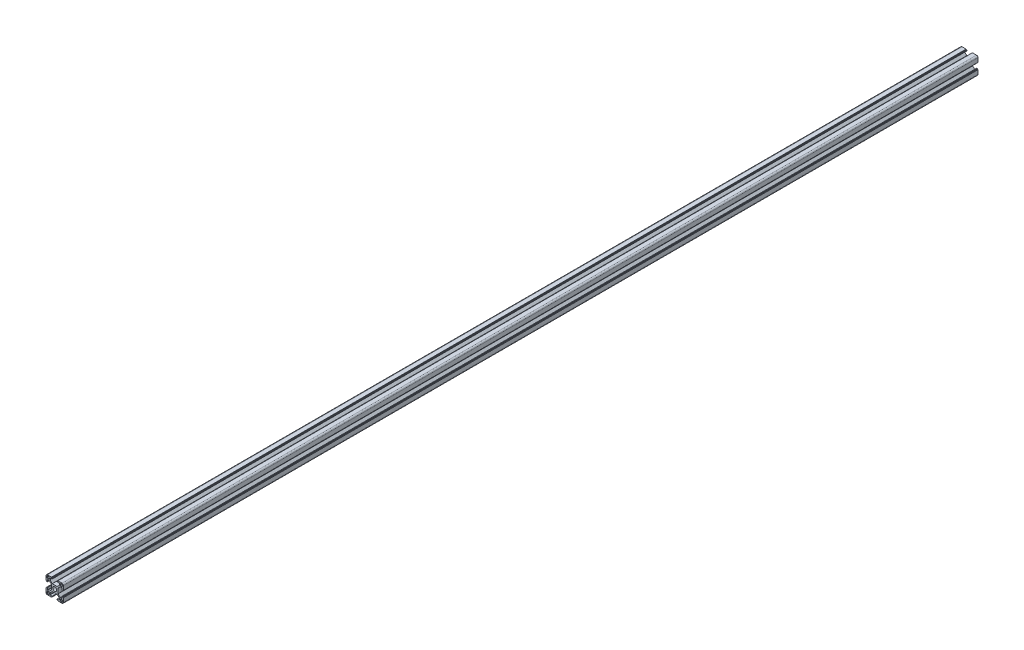
SolidWorks part; units mm, degrees
ref_plane "Front Plane" through (0, 0, 0) normal (0, 0, 1) x (1, 0, 0)
ref_plane "Top Plane" through (0, 0, 0) normal (0, 1, 0) x (1, 0, 0)
ref_plane "Right Plane" through (0, 0, 0) normal (1, 0, 0) x (0, 0, -1)
sketch "Model" plane through (0, 0, 0) normal (0, 0, 1) x (1, 0, 0)
  line L0 (21.5, 27) -> (25, 27)
  line L1 (27, 25) -> (27, 21.5)
  line L2 (25, 19.5) -> (21.5, 19.5)
  line L3 (19.5, 21.5) -> (19.5, 25)
  line L4 (21.5, -27) -> (25, -27)
  line L5 (27, -25) -> (27, -21.5)
  line L6 (25, -19.5) -> (21.5, -19.5)
  line L7 (19.5, -21.5) -> (19.5, -25)
  line L8 (0, 11.6) -> (-8.2402, 11.6)
  line L9 (-8.6645, 11.7757) -> (-16.3243, 19.4355)
  line L10 (-16.5, 19.8598) -> (-16.5, 25)
  line L11 (-15.9, 25.6) -> (-8.8, 25.6)
  line L12 (-8.2, 26.2) -> (-8.2, 27.4)
  line L13 (-8.8, 28) -> (-9.8, 28)
  line L14 (-10.4, 28.6) -> (-10.4, 29.4)
  line L15 (-11, 30) -> (-25, 30)
  line L16 (-30, 25) -> (-30, 11)
  line L17 (-29.4, 10.4) -> (-28.6, 10.4)
  line L18 (-28, 9.8) -> (-28, 8.8)
  line L19 (-27.4, 8.2) -> (-26.2, 8.2)
  line L20 (-25.6, 8.8) -> (-25.6, 15.9)
  line L21 (-25, 16.5) -> (-19.8598, 16.5)
  line L22 (-19.4355, 16.3243) -> (-11.7757, 8.6645)
  line L23 (-11.6, 8.2402) -> (-11.6, 0)
  line L24 (-11.6, 0) -> (-11.6, -8.2402)
  line L25 (-11.7757, -8.6645) -> (-19.4355, -16.3243)
  line L26 (-19.8598, -16.5) -> (-25, -16.5)
  line L27 (-25.6, -15.9) -> (-25.6, -8.8)
  line L28 (-26.2, -8.2) -> (-27.4, -8.2)
  line L29 (-28, -8.8) -> (-28, -9.8)
  line L30 (-28.6, -10.4) -> (-29.4, -10.4)
  line L31 (-30, -11) -> (-30, -25)
  line L32 (-25, -30) -> (-11, -30)
  line L33 (-10.4, -29.4) -> (-10.4, -28.6)
  line L34 (-9.8, -28) -> (-8.8, -28)
  line L35 (-8.2, -27.4) -> (-8.2, -26.2)
  line L36 (-8.8, -25.6) -> (-15.9, -25.6)
  line L37 (-16.5, -25) -> (-16.5, -19.8598)
  line L38 (-16.3243, -19.4355) -> (-8.6645, -11.7757)
  line L39 (-8.2402, -11.6) -> (0, -11.6)
  line L40 (0, -11.6) -> (8.2402, -11.6)
  line L41 (8.6645, -11.7757) -> (16.3243, -19.4355)
  line L42 (16.5, -19.8598) -> (16.5, -25)
  line L43 (15.9, -25.6) -> (8.8, -25.6)
  line L44 (8.2, -26.2) -> (8.2, -27.4)
  line L45 (8.8, -28) -> (9.8, -28)
  line L46 (10.4, -28.6) -> (10.4, -29.4)
  line L47 (11, -30) -> (25, -30)
  line L48 (30, -25) -> (30, -11)
  line L49 (29.4, -10.4) -> (28.6, -10.4)
  line L50 (28, -9.8) -> (28, -8.8)
  line L51 (27.4, -8.2) -> (26.2, -8.2)
  line L52 (25.6, -8.8) -> (25.6, -15.9)
  line L53 (25, -16.5) -> (19.8598, -16.5)
  line L54 (19.4355, -16.3243) -> (11.7757, -8.6645)
  line L55 (11.6, -8.2402) -> (11.6, 0)
  line L56 (11.6, 0) -> (11.6, 8.2402)
  line L57 (11.7757, 8.6645) -> (19.6113, 16.5)
  line L58 (19.6113, 16.5) -> (25, 16.5)
  line L59 (25.6, 15.9) -> (25.6, 8.8)
  line L60 (26.2, 8.2) -> (27.4, 8.2)
  line L61 (28, 8.8) -> (28, 9.8)
  line L62 (28.6, 10.4) -> (29.4, 10.4)
  line L63 (30, 11) -> (30, 25)
  line L64 (25, 30) -> (11, 30)
  line L65 (10.4, 29.4) -> (10.4, 28.6)
  line L66 (9.8, 28) -> (8.8, 28)
  line L67 (8.2, 27.4) -> (8.2, 26.2)
  line L68 (8.8, 25.6) -> (15.9, 25.6)
  line L69 (16.5, 25) -> (16.5, 19.8598)
  line L70 (16.3243, 19.4355) -> (8.6645, 11.7757)
  line L71 (8.2402, 11.6) -> (0, 11.6)
  line L72 (-21.5, -27) -> (-25, -27)
  line L73 (-27, -25) -> (-27, -21.5)
  line L74 (-25, -19.5) -> (-21.5, -19.5)
  line L75 (-19.5, -21.5) -> (-19.5, -25)
  line L76 (-21.5, 27) -> (-25, 27)
  line L77 (-27, 25) -> (-27, 21.5)
  line L78 (-25, 19.5) -> (-21.5, 19.5)
  line L79 (-19.5, 21.5) -> (-19.5, 25)
  circle A0 centre (0, 0) radius 6.8
  arc A1 (21.5, 27) -> (19.5, 25) centre (21.5, 25) ccw
  arc A2 (27, 25) -> (25, 27) centre (25, 25) ccw
  arc A3 (25, 19.5) -> (27, 21.5) centre (25, 21.5) ccw
  arc A4 (19.5, 21.5) -> (21.5, 19.5) centre (21.5, 21.5) ccw
  arc A5 (19.5, -25) -> (21.5, -27) centre (21.5, -25) ccw
  arc A6 (25, -27) -> (27, -25) centre (25, -25) ccw
  arc A7 (27, -21.5) -> (25, -19.5) centre (25, -21.5) ccw
  arc A8 (21.5, -19.5) -> (19.5, -21.5) centre (21.5, -21.5) ccw
  arc A9 (-8.6645, 11.7757) -> (-8.2402, 11.6) centre (-8.2402, 12.2) ccw
  arc A10 (-16.5, 19.8598) -> (-16.3243, 19.4355) centre (-15.9, 19.8598) ccw
  arc A11 (-15.9, 25.6) -> (-16.5, 25) centre (-15.9, 25) ccw
  arc A12 (-8.8, 25.6) -> (-8.2, 26.2) centre (-8.8, 26.2) ccw
  arc A13 (-8.2, 27.4) -> (-8.8, 28) centre (-8.8, 27.4) ccw
  arc A14 (-10.4, 28.6) -> (-9.8, 28) centre (-9.8, 28.6) ccw
  arc A15 (-10.4, 29.4) -> (-11, 30) centre (-11, 29.4) ccw
  arc A16 (-25, 30) -> (-30, 25) centre (-25, 25) ccw
  arc A17 (-30, 11) -> (-29.4, 10.4) centre (-29.4, 11) ccw
  arc A18 (-28, 9.8) -> (-28.6, 10.4) centre (-28.6, 9.8) ccw
  arc A19 (-28, 8.8) -> (-27.4, 8.2) centre (-27.4, 8.8) ccw
  arc A20 (-26.2, 8.2) -> (-25.6, 8.8) centre (-26.2, 8.8) ccw
  arc A21 (-25, 16.5) -> (-25.6, 15.9) centre (-25, 15.9) ccw
  arc A22 (-19.4355, 16.3243) -> (-19.8598, 16.5) centre (-19.8598, 15.9) ccw
  arc A23 (-11.6, 8.2402) -> (-11.7757, 8.6645) centre (-12.2, 8.2402) ccw
  arc A24 (-11.7757, -8.6645) -> (-11.6, -8.2402) centre (-12.2, -8.2402) ccw
  arc A25 (-19.8598, -16.5) -> (-19.4355, -16.3243) centre (-19.8598, -15.9) ccw
  arc A26 (-25.6, -15.9) -> (-25, -16.5) centre (-25, -15.9) ccw
  arc A27 (-25.6, -8.8) -> (-26.2, -8.2) centre (-26.2, -8.8) ccw
  arc A28 (-27.4, -8.2) -> (-28, -8.8) centre (-27.4, -8.8) ccw
  arc A29 (-28.6, -10.4) -> (-28, -9.8) centre (-28.6, -9.8) ccw
  arc A30 (-29.4, -10.4) -> (-30, -11) centre (-29.4, -11) ccw
  arc A31 (-30, -25) -> (-25, -30) centre (-25, -25) ccw
  arc A32 (-11, -30) -> (-10.4, -29.4) centre (-11, -29.4) ccw
  arc A33 (-9.8, -28) -> (-10.4, -28.6) centre (-9.8, -28.6) ccw
  arc A34 (-8.8, -28) -> (-8.2, -27.4) centre (-8.8, -27.4) ccw
  arc A35 (-8.2, -26.2) -> (-8.8, -25.6) centre (-8.8, -26.2) ccw
  arc A36 (-16.5, -25) -> (-15.9, -25.6) centre (-15.9, -25) ccw
  arc A37 (-16.3243, -19.4355) -> (-16.5, -19.8598) centre (-15.9, -19.8598) ccw
  arc A38 (-8.2402, -11.6) -> (-8.6645, -11.7757) centre (-8.2402, -12.2) ccw
  arc A39 (8.6645, -11.7757) -> (8.2402, -11.6) centre (8.2402, -12.2) ccw
  arc A40 (16.5, -19.8598) -> (16.3243, -19.4355) centre (15.9, -19.8598) ccw
  arc A41 (15.9, -25.6) -> (16.5, -25) centre (15.9, -25) ccw
  arc A42 (8.8, -25.6) -> (8.2, -26.2) centre (8.8, -26.2) ccw
  arc A43 (8.2, -27.4) -> (8.8, -28) centre (8.8, -27.4) ccw
  arc A44 (10.4, -28.6) -> (9.8, -28) centre (9.8, -28.6) ccw
  arc A45 (10.4, -29.4) -> (11, -30) centre (11, -29.4) ccw
  arc A46 (25, -30) -> (30, -25) centre (25, -25) ccw
  arc A47 (30, -11) -> (29.4, -10.4) centre (29.4, -11) ccw
  arc A48 (28, -9.8) -> (28.6, -10.4) centre (28.6, -9.8) ccw
  arc A49 (28, -8.8) -> (27.4, -8.2) centre (27.4, -8.8) ccw
  arc A50 (26.2, -8.2) -> (25.6, -8.8) centre (26.2, -8.8) ccw
  arc A51 (25, -16.5) -> (25.6, -15.9) centre (25, -15.9) ccw
  arc A52 (19.4355, -16.3243) -> (19.8598, -16.5) centre (19.8598, -15.9) ccw
  arc A53 (11.6, -8.2402) -> (11.7757, -8.6645) centre (12.2, -8.2402) ccw
  arc A54 (11.7757, 8.6645) -> (11.6, 8.2402) centre (12.2, 8.2402) ccw
  arc A55 (25.6, 15.9) -> (25, 16.5) centre (25, 15.9) ccw
  arc A56 (25.6, 8.8) -> (26.2, 8.2) centre (26.2, 8.8) ccw
  arc A57 (27.4, 8.2) -> (28, 8.8) centre (27.4, 8.8) ccw
  arc A58 (28.6, 10.4) -> (28, 9.8) centre (28.6, 9.8) ccw
  arc A59 (29.4, 10.4) -> (30, 11) centre (29.4, 11) ccw
  arc A60 (30, 25) -> (25, 30) centre (25, 25) ccw
  arc A61 (11, 30) -> (10.4, 29.4) centre (11, 29.4) ccw
  arc A62 (9.8, 28) -> (10.4, 28.6) centre (9.8, 28.6) ccw
  arc A63 (8.8, 28) -> (8.2, 27.4) centre (8.8, 27.4) ccw
  arc A64 (8.2, 26.2) -> (8.8, 25.6) centre (8.8, 26.2) ccw
  arc A65 (16.5, 25) -> (15.9, 25.6) centre (15.9, 25) ccw
  arc A66 (16.3243, 19.4355) -> (16.5, 19.8598) centre (15.9, 19.8598) ccw
  arc A67 (8.2402, 11.6) -> (8.6645, 11.7757) centre (8.2402, 12.2) ccw
  arc A68 (-21.5, -27) -> (-19.5, -25) centre (-21.5, -25) ccw
  arc A69 (-27, -25) -> (-25, -27) centre (-25, -25) ccw
  arc A70 (-25, -19.5) -> (-27, -21.5) centre (-25, -21.5) ccw
  arc A71 (-19.5, -21.5) -> (-21.5, -19.5) centre (-21.5, -21.5) ccw
  arc A72 (-19.5, 25) -> (-21.5, 27) centre (-21.5, 25) ccw
  arc A73 (-25, 27) -> (-27, 25) centre (-25, 25) ccw
  arc A74 (-27, 21.5) -> (-25, 19.5) centre (-25, 21.5) ccw
  arc A75 (-21.5, 19.5) -> (-19.5, 21.5) centre (-21.5, 21.5) ccw
extrude "Boss-Extrude1" add sketch "Model" along normal blind 3150
scale "Scale1" bodies to scale 101 scale about centroid uniform scaling yes scale factor 0.333333
